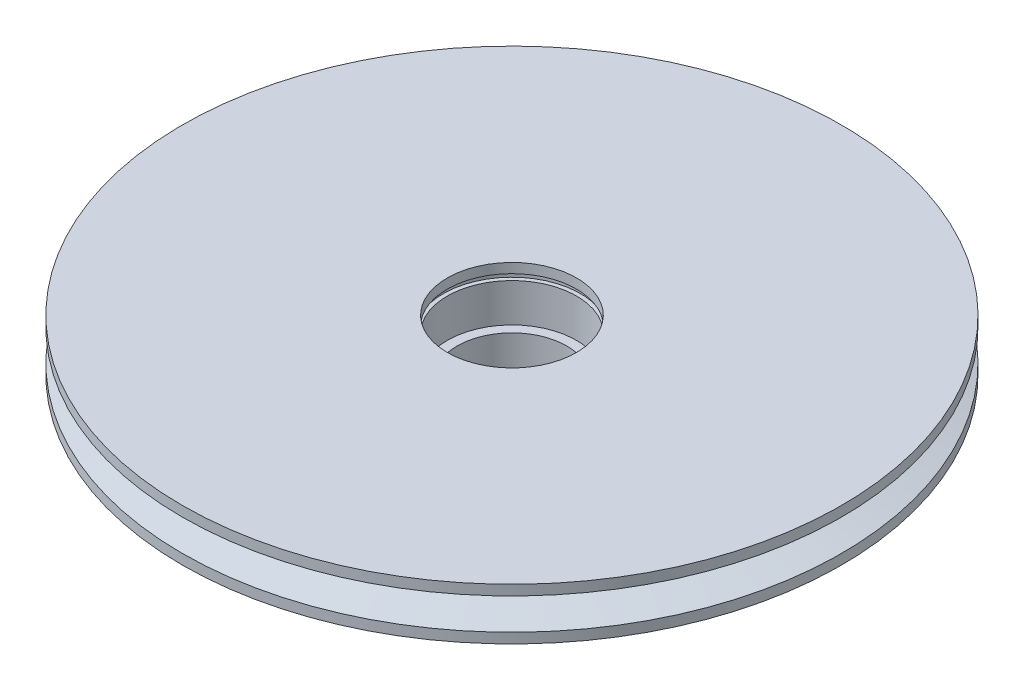
SolidWorks part; units mm, degrees
ref_plane "Front Plane" through (0, 0, 0) normal (0, 0, 1) x (1, 0, 0)
ref_plane "Top Plane" through (0, 0, 0) normal (0, 1, 0) x (1, 0, 0)
ref_plane "Right Plane" through (0, 0, 0) normal (1, 0, 0) x (0, 0, -1)
sketch "Sketch1" plane through (0, 0, 0) normal (0, 0, 1) x (1, 0, 0)
  line L0 (0, 42.1053) -> (0, 0) construction
  line L1 (17, 30.1115) -> (17, 16.75)
  line L2 (20, 0) -> (39.5, 0)
  line L3 (39.5, 0) -> (39.5, 3.1385)
  line L4 (39.5, 3.1385) -> (28.5, 6.5016)
  line L5 (28.5, 6.5016) -> (28.5, 9.4984)
  line L6 (28.5, 9.4984) -> (39.5, 12.8615)
  line L7 (39.5, 12.8615) -> (39.5, 15.1385)
  line L8 (39.5, 15.1385) -> (28.5, 18.5016)
  line L9 (28.5, 18.5016) -> (28.5, 21.4984)
  line L10 (28.5, 21.4984) -> (39.5, 24.8615)
  line L11 (39.5, 24.8615) -> (39.5, 30.8615)
  line L15 (37.5, 30.1194) -> (37.5, -2.7923) construction
  line L16 (39.5, 8) -> (0, 8) construction
  line L17 (39.5, 20) -> (0, 20) construction
  line L18 (102, 30.8615) -> (39.5, 30.8615)
  line L19 (102, 30.8615) -> (102, 34)
  line L20 (102, 34) -> (91, 37.363)
  line L21 (91, 37.363) -> (91, 40.3599)
  line L22 (91, 40.3599) -> (102, 43.7229)
  line L23 (102, 43.7229) -> (102, 46.8615)
  line L24 (102, 46.8615) -> (20, 46.8615)
  line L26 (100, 44.3643) -> (100, 27.5744) construction
  line L27 (102, 38.8615) -> (0, 38.8615) construction
  line L28 (20, 46.8615) -> (20, 43.8615)
  line L29 (20, 30.1115) -> (17, 30.1115)
  line L30 (17, 16.75) -> (20, 16.75)
  line L31 (20, 16.75) -> (20, 4.85)
  line L32 (20, 43.8615) -> (21.25, 43.8615)
  line L33 (21.25, 43.8615) -> (21.25, 42.0115)
  line L34 (21.25, 42.0115) -> (20, 42.0115)
  line L35 (20, 42.0115) -> (20, 30.1115)
  line L36 (20, 4.85) -> (21.25, 4.85)
  line L37 (21.25, 4.85) -> (21.25, 3)
  line L38 (21.25, 3) -> (20, 3)
  line L39 (20, 3) -> (20, 0)
  point P23 (28.5, 20)
  point P24 (28.5, 8)
  point P25 (37.5, 24.25)
  point P26 (37.5, 15.75)
  point P27 (37.5, 12.25)
  point P28 (37.5, 3.75)
  point P33 (100, 34.6115)
  point P38 (91, 38.8615)
  point P39 (100, 43.1115)
  dimension "D2" = 34
  dimension "D3" = 75
  dimension "D4" = 9
  dimension "D5" = 8
  dimension "D6" = 12
  dimension "D7" = 2
  dimension "D8" = 8.5
  dimension "D10" = 34
  dimension "D11" = 2
  dimension "D12" = 9
  dimension "D9" = 8.5
  dimension "D13" = 8
  dimension "D14" = 200
  dimension "D16" = 6
  dimension "D17" = 1.85
  dimension "D18" = 3
  dimension "D19" = 42.5
  dimension "D20" = 40
  dimension "D21" = 34
  dimension "D15" = 13.75
revolve "Revolve1" add sketch "Sketch1" angle 360 about L0
equation "\"f_poulie_receptrice\"=8"
equation "\"D5@Sketch1\"=\"f_poulie_receptrice\""
equation "\"e_poulie_receptrice\"=12"
equation "\"D6@Sketch1\"=\"e_poulie_receptrice\""
equation "\"b_poulie_receptrice\"=2"
equation "\"D7@Sketch1\"=\"b_poulie_receptrice\""
equation "\"h_gorge_poulie_receptrice\"=9"
equation "\"D4@Sketch1\"=\"h_gorge_poulie_receptrice\""
equation "\"W_poulie_receptrice\"=8.5"
equation "\"D8@Sketch1\"=\"W_poulie_receptrice\""
